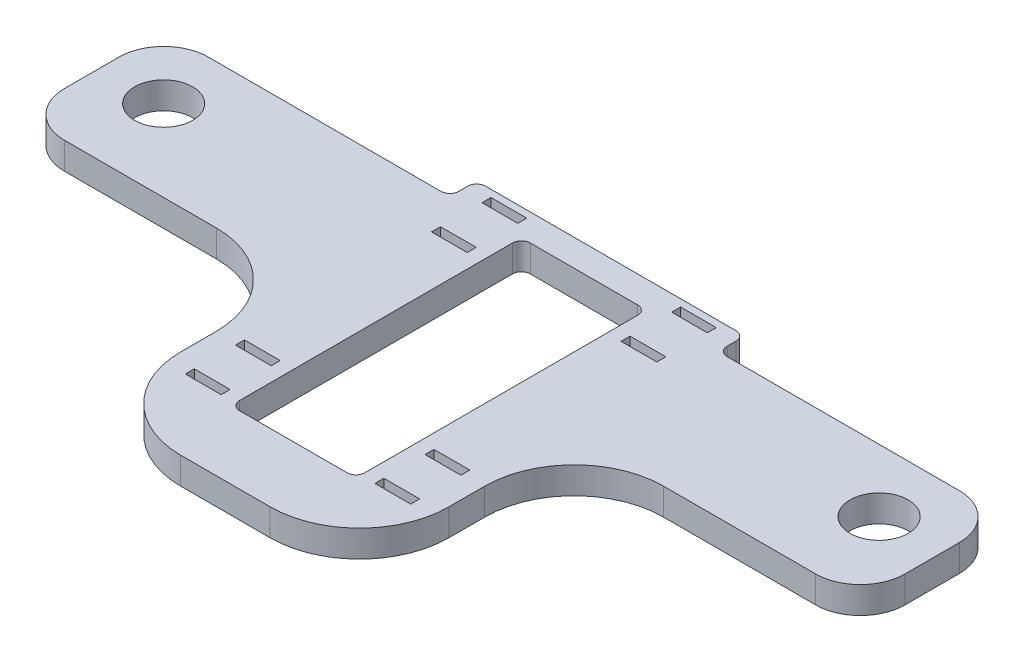
SolidWorks part; units mm, degrees
ref_plane "Front Plane" through (0, 0, 0) normal (0, 0, 1) x (1, 0, 0)
ref_plane "Top Plane" through (0, 0, 0) normal (0, 1, 0) x (1, 0, 0)
ref_plane "Right Plane" through (0, 0, 0) normal (1, 0, 0) x (0, 0, -1)
sketch "Sketch1" plane through (0, 0, 0) normal (0, 1, 0) x (1, 0, 0)
  line L0 (0, 43.1) -> (0, 40.1) construction
  line L1 (-47, 40.1) -> (-15, 40.1)
  line L2 (-47, 40.1) -> (-47, 24)
  line L4 (47, 40.1) -> (47, 24)
  line L5 (15, 0) -> (15, 24)
  line L6 (15, 24) -> (47, 24)
  line L11 (-15, 40.1) -> (-15, 43.1)
  line L13 (-15, 43.1) -> (15, 43.1)
  line L15 (15, 43.1) -> (15, 40.1)
  line L16 (15, 40.1) -> (47, 40.1)
  line L17 (-7, 40.1) -> (7, 40.1)
  line L18 (-7, 40.1) -> (-7, 7.6)
  line L19 (-7, 7.6) -> (7, 7.6)
  line L20 (7, 40.1) -> (7, 7.6)
  line L22 (15, 0) -> (-15, 0)
  line L23 (-15, 0) -> (-15, 24)
  line L24 (-15, 24) -> (-47, 24)
  line L25 (0, 0) -> (0, 7.6) construction
  circle A0 centre (40, 33.1) radius 3.25
  circle A1 centre (-40, 33.1) radius 3.25
  point P0 (0, 40.1)
  point P22 (0, 43.1)
  point P27 (0, 40.1)
  dimension "D7" = 7
  dimension "D11" = 6.5
  dimension "D1" = 30
  dimension "D2" = 3
  dimension "D3" = 94
  dimension "D4" = 14
  dimension "D5" = 24
  dimension "D6" = 32.5
  dimension "D8" = 7.6
  dimension "D9" = 30
  dimension "D10" = 40
extrude "Boss-Extrude1" add sketch "Sketch1" along normal blind 3 contours L6 L4 L16 L15 L13 L11 L1 L2 L24 L23 L22 L5
fillet "Fillet1" radius 10 4 edges at (-15, 1.5, -24) (15, 1.5, -24) (15, 1.5, 0) (-15, 1.5, 0)
fillet "Fillet2" radius 1 8 edges at (7, 1.5, -40.1) (-7, 1.5, -40.1) (7, 1.5, -7.6) (-7, 1.5, -7.6) (-15, 1.5, -43.1) (-15, 1.5, -40.1) (15, 1.5, -43.1) (15, 1.5, -40.1)
fillet "Fillet3" radius 5 4 edges at (-47, 1.5, -24) (-47, 1.5, -40.1) (47, 1.5, -24) (47, 1.5, -40.1)
sketch "Sketch2" plane through (0, 3, 0) normal (0, 1, 0) x (1, 0, 0)
  line L0 (8.6, 13.725) -> (12.6, 13.725)
  line L1 (8.6, 41.3) -> (12.6, 41.3)
  line L2 (8.6, 41.3) -> (8.6, 42.3)
  line L3 (8.6, 42.3) -> (12.6, 42.3)
  line L4 (12.6, 41.3) -> (12.6, 42.3)
  line L5 (8.6, 13.725) -> (8.6, 14.725)
  line L6 (8.6, 14.725) -> (12.6, 14.725)
  line L7 (14, 43.1) -> (-14, 43.1) construction
  line L8 (15, 41.1) -> (15, 42.1) construction
  line L9 (0, 43.1) -> (0, 40.1) construction
  line L10 (-12.6, 41.3) -> (-12.6, 42.3)
  line L11 (-8.6, 42.3) -> (-12.6, 42.3)
  line L12 (-8.6, 41.3) -> (-8.6, 42.3)
  line L13 (-8.6, 41.3) -> (-12.6, 41.3)
  line L14 (6, 40.1) -> (-6, 40.1) construction
  line L15 (7, 38.975) -> (-7, 38.975) construction
  line L16 (7, 8.6) -> (7, 39.1) construction
  line L17 (-7, 39.1) -> (-7, 8.6) construction
  line L18 (12.6, 13.725) -> (12.6, 14.725)
  line L19 (-8.6, 36.65) -> (-12.6, 36.65)
  line L20 (-8.6, 36.65) -> (-8.6, 35.65)
  line L21 (-8.6, 35.65) -> (-12.6, 35.65)
  line L22 (-12.6, 36.65) -> (-12.6, 35.65)
  line L23 (12.6, 36.65) -> (12.6, 35.65)
  line L24 (8.6, 35.65) -> (12.6, 35.65)
  line L25 (8.6, 36.65) -> (8.6, 35.65)
  line L26 (8.6, 36.65) -> (12.6, 36.65)
  line L27 (0, 15.4976) -> (0, 12.4976) construction
  line L28 (-12.6, 13.725) -> (-12.6, 14.725)
  line L29 (-8.6, 14.725) -> (-12.6, 14.725)
  line L30 (-8.6, 13.725) -> (-8.6, 14.725)
  line L31 (-8.6, 13.725) -> (-12.6, 13.725)
  line L32 (15, 11.425) -> (-15, 11.425) construction
  line L33 (-8.6, 9.125) -> (-12.6, 9.125)
  line L34 (-8.6, 9.125) -> (-8.6, 8.125)
  line L35 (-8.6, 8.125) -> (-12.6, 8.125)
  line L36 (-12.6, 9.125) -> (-12.6, 8.125)
  line L37 (12.6, 9.125) -> (12.6, 8.125)
  line L38 (8.6, 8.125) -> (12.6, 8.125)
  line L39 (8.6, 9.125) -> (8.6, 8.125)
  line L40 (8.6, 9.125) -> (12.6, 9.125)
  line L41 (15, 9.2) -> (15, 13.65) construction
  line L42 (-15, 14) -> (-15, 10) construction
  dimension "D1" = 4
  dimension "D2" = 1
  dimension "D3" = 0.8
  dimension "D4" = 2.4
  dimension "D5" = 4.125
  dimension "D6" = 4
  dimension "D7" = 2.3
extrude "Cut-Extrude1" cut sketch "Sketch2" against normal up to next
